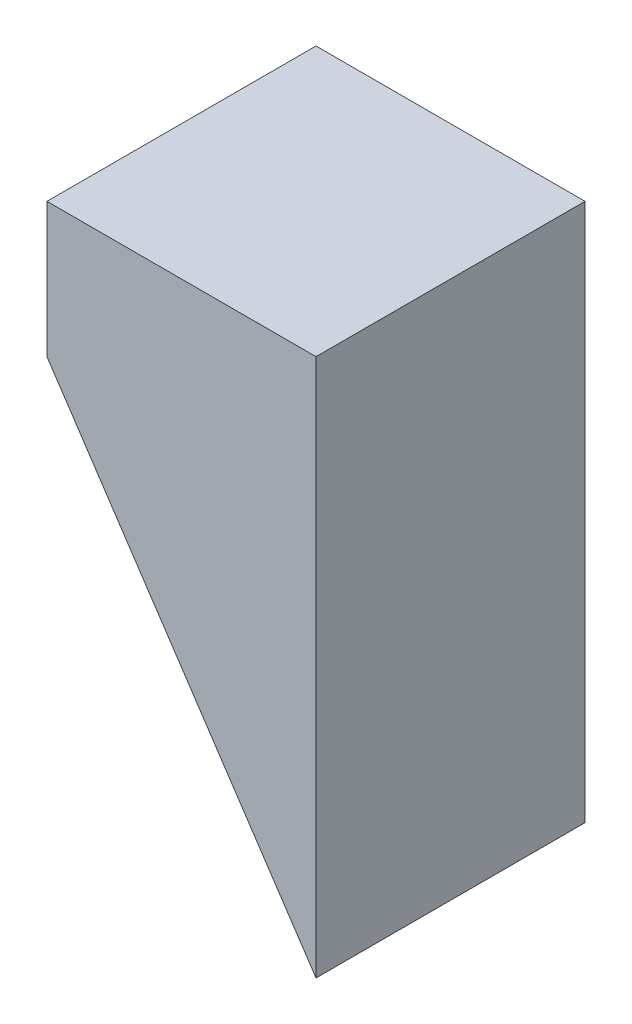
SolidWorks part; units mm, degrees
ref_plane "前基準面" through (0, 0, 0) normal (0, 0, 1) x (1, 0, 0)
ref_plane "上基準面" through (0, 0, 0) normal (0, 1, 0) x (1, 0, 0)
ref_plane "右基準面" through (0, 0, 0) normal (1, 0, 0) x (0, 0, -1)
sketch "草圖1" plane through (0, 0, 0) normal (0, 0, 1) x (1, 0, 0)
  line L0 (-18.9403, 5.5686) -> (11.0597, -39.4314)
  line L1 (-18.9403, 20.5686) -> (11.0597, 20.5686)
  line L2 (-18.9403, 20.5686) -> (-18.9403, 5.5686)
  line L4 (11.0597, 20.5686) -> (11.0597, -39.4314)
  dimension "D1" = 15
  dimension "D2" = 30
extrude "填料-伸長1" add sketch "草圖1" along normal blind 30
sketch "草圖2" plane through (-18.9403, 0, 0) normal (-1, 0, 0) x (0, 0, 1)
  line L0 (30, 5.5686) -> (30, -39.4314) construction
  line L1 (5, 1.8713) -> (25, 1.8713)
  line L2 (5, 1.8713) -> (5, -28.3971)
  line L3 (5, -28.3971) -> (25, -28.3971)
  line L4 (25, 1.8713) -> (25, -28.3971)
  line L5 (0, 5.5686) -> (0, -39.4314) construction
  dimension "D1" = 5
  dimension "D2" = 5
extrude "除料-伸長1" cut sketch "草圖2" against normal blind 27
sketch "草圖3" plane through (8.0597, 0, 0) normal (-1, 0, 0) x (0, 0, 1)
  line L0 (30, 5.5686) -> (30, -39.4314) construction
  line L1 (30, 20.5686) -> (0, 20.5686) construction
  circle A0 centre (14.6169, -1.9314) radius 2.75
  dimension "D1" = 5.5
  dimension "D2" = 15.3831
  dimension "D3" = 22.5
